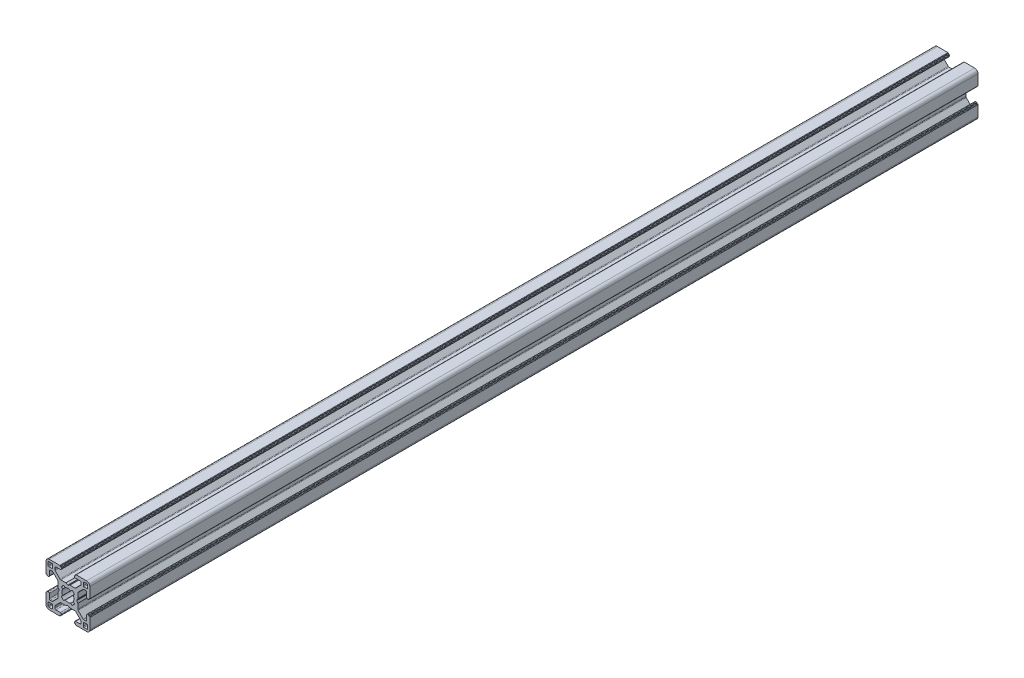
SolidWorks part; units mm, degrees
material "6063-O, Barra estrusa (SS)"
ref_plane "Piano frontale" through (0, 0, 0) normal (0, 0, 1) x (1, 0, 0)
ref_plane "Piano superiore" through (0, 0, 0) normal (0, 1, 0) x (1, 0, 0)
ref_plane "Piano destro" through (0, 0, 0) normal (1, 0, 0) x (0, 0, -1)
ref_plane "Piano1" through (0, 0, 100) normal (0, 0, 1) x (1, 0, 0)
sketch "Schizzo1" plane through (0, 0, 100) normal (0, 0, 1) x (1, 0, 0)
  line L0 (-1.9139, 2.9896) -> (-1.2582, 2.4453)
  line L1 (1.2582, 2.4453) -> (1.9139, 2.9896)
  line L2 (2.9922, 1.9099) -> (2.4453, 1.2582)
  line L3 (2.4453, -1.2582) -> (2.9922, -1.9099)
  line L4 (1.9139, -2.9896) -> (1.2582, -2.4453)
  line L5 (-1.2582, -2.4453) -> (-1.9139, -2.9896)
  line L6 (-2.9922, -1.9099) -> (-2.4453, -1.2582)
  line L7 (-2.4453, 1.2582) -> (-2.9922, 1.9099)
  line L8 (-9.3, 3) -> (-9, 3)
  line L9 (-8.5, 3.5) -> (-8.5, 5.5)
  line L10 (-8, 6) -> (-7.2678, 6)
  line L11 (-6.9142, 5.8536) -> (-4.6464, 3.5858)
  line L12 (-4.5, 3.2322) -> (-4.5, 0.9536)
  line L13 (-4.4732, 0.8536) -> (-4.0381, 0.1)
  line L14 (-4.0381, -0.1) -> (-4.4732, -0.8536)
  line L15 (-4.5, -0.9536) -> (-4.5, -3.2322)
  line L16 (-4.6464, -3.5858) -> (-6.9142, -5.8536)
  line L17 (-7.2678, -6) -> (-8, -6)
  line L18 (-8.5, -5.5) -> (-8.5, -3.5)
  line L19 (-9, -3) -> (-9.3, -3)
  line L20 (-9.5, -3.2) -> (-9.5, -3.35)
  line L21 (-9.7, -3.55) -> (-9.8, -3.55)
  line L22 (-10, -3.75) -> (-10, -8.5)
  line L23 (-8.5, -10) -> (-3.75, -10)
  line L24 (-3.55, -9.8) -> (-3.55, -9.7)
  line L25 (-3.35, -9.5) -> (-3.2, -9.5)
  line L26 (-3, -9.3) -> (-3, -9)
  line L27 (-3.5, -8.5) -> (-5.5, -8.5)
  line L28 (-6, -8) -> (-6, -7.2678)
  line L29 (-5.8536, -6.9142) -> (-3.5858, -4.6464)
  line L30 (-3.2322, -4.5) -> (-0.9536, -4.5)
  line L31 (-0.8536, -4.4732) -> (-0.1, -4.0381)
  line L32 (0.1, -4.0381) -> (0.8536, -4.4732)
  line L33 (0.9536, -4.5) -> (3.2322, -4.5)
  line L34 (3.5858, -4.6464) -> (5.8536, -6.9142)
  line L35 (6, -7.2678) -> (6, -8)
  line L36 (5.5, -8.5) -> (3.5, -8.5)
  line L37 (3, -9) -> (3, -9.3)
  line L38 (3.2, -9.5) -> (3.35, -9.5)
  line L39 (3.55, -9.7) -> (3.55, -9.8)
  line L40 (3.75, -10) -> (8.5, -10)
  line L41 (10, -8.5) -> (10, -3.75)
  line L42 (9.8, -3.55) -> (9.7, -3.55)
  line L43 (9.5, -3.35) -> (9.5, -3.2)
  line L44 (9.3, -3) -> (9, -3)
  line L45 (8.5, -3.5) -> (8.5, -5.5)
  line L46 (8, -6) -> (7.2678, -6)
  line L47 (6.9142, -5.8536) -> (4.6464, -3.5858)
  line L48 (4.5, -3.2322) -> (4.5, -0.9536)
  line L49 (4.4732, -0.8536) -> (4.0381, -0.1)
  line L50 (4.0381, 0.1) -> (4.4732, 0.8536)
  line L51 (4.5, 0.9536) -> (4.5, 3.2322)
  line L52 (4.6464, 3.5858) -> (6.9142, 5.8536)
  line L53 (7.2678, 6) -> (8, 6)
  line L54 (8.5, 5.5) -> (8.5, 3.5)
  line L55 (9, 3) -> (9.3, 3)
  line L56 (9.5, 3.2) -> (9.5, 3.35)
  line L57 (9.7, 3.55) -> (9.8, 3.55)
  line L58 (10, 3.75) -> (10, 8.5)
  line L59 (8.5, 10) -> (3.75, 10)
  line L60 (3.55, 9.8) -> (3.55, 9.7)
  line L61 (3.35, 9.5) -> (3.2, 9.5)
  line L62 (3, 9.3) -> (3, 9)
  line L63 (3.5, 8.5) -> (5.5, 8.5)
  line L64 (6, 8) -> (6, 7.2678)
  line L65 (5.8536, 6.9142) -> (3.5858, 4.6464)
  line L66 (3.2322, 4.5) -> (0.9536, 4.5)
  line L67 (0.8536, 4.4732) -> (0.1, 4.0381)
  line L68 (-0.1, 4.0381) -> (-0.8536, 4.4732)
  line L69 (-0.9536, 4.5) -> (-3.2322, 4.5)
  line L70 (-3.5858, 4.6464) -> (-5.8536, 6.9142)
  line L71 (-6, 7.2678) -> (-6, 8)
  line L72 (-5.5, 8.5) -> (-3.5, 8.5)
  line L73 (-3, 9) -> (-3, 9.3)
  line L74 (-3.2, 9.5) -> (-3.35, 9.5)
  line L75 (-3.55, 9.7) -> (-3.55, 9.8)
  line L76 (-3.75, 10) -> (-8.5, 10)
  line L77 (-10, 8.5) -> (-10, 3.75)
  line L78 (-9.8, 3.55) -> (-9.7, 3.55)
  line L79 (-9.5, 3.35) -> (-9.5, 3.2)
  line L80 (8.7, 7) -> (7.3, 7)
  line L81 (-7.3, 7) -> (-8.7, 7)
  line L82 (-7, 7.3) -> (-7, 8.7)
  line L83 (-7.3, 9) -> (-8.7, 9)
  line L84 (-9, 7.3) -> (-9, 8.7)
  line L85 (9, 7.3) -> (9, 8.7)
  line L86 (8.7, 9) -> (7.3, 9)
  line L87 (7, 7.3) -> (7, 8.7)
  line L88 (8.7, -9) -> (7.3, -9)
  line L89 (9, -8.7) -> (9, -7.3)
  line L90 (8.7, -7) -> (7.3, -7)
  line L91 (7, -8.7) -> (7, -7.3)
  line L92 (-7.3, -9) -> (-8.7, -9)
  line L93 (-7, -8.7) -> (-7, -7.3)
  line L94 (-7.3, -7) -> (-8.7, -7)
  line L95 (-9, -8.7) -> (-9, -7.3)
  arc A0 (-1.2582, 2.4453) -> (1.2582, 2.4453) centre (0, 0) cw
  arc A1 (1.9139, 2.9896) -> (2.9922, 1.9099) centre (0, 0) cw
  arc A2 (2.4453, 1.2582) -> (2.4453, -1.2582) centre (0, 0) cw
  arc A3 (2.9922, -1.9099) -> (1.9139, -2.9896) centre (0, 0) cw
  arc A4 (1.2582, -2.4453) -> (-1.2582, -2.4453) centre (0, 0) cw
  arc A5 (-1.9139, -2.9896) -> (-2.9922, -1.9099) centre (0, 0) cw
  arc A6 (-2.4453, -1.2582) -> (-2.4453, 1.2582) centre (0, 0) cw
  arc A7 (-2.9922, 1.9099) -> (-1.9139, 2.9896) centre (0, 0) cw
  arc A8 (-9.5, 3.2) -> (-9.3, 3) centre (-9.3, 3.2) ccw
  arc A9 (-9, 3) -> (-8.5, 3.5) centre (-9, 3.5) ccw
  arc A10 (-8.5, 5.5) -> (-8, 6) centre (-8, 5.5) cw
  arc A11 (-7.2678, 6) -> (-6.9142, 5.8536) centre (-7.2678, 5.5) cw
  arc A12 (-4.6464, 3.5858) -> (-4.5, 3.2322) centre (-5, 3.2322) cw
  arc A13 (-4.5, 0.9536) -> (-4.4732, 0.8536) centre (-4.3, 0.9536) ccw
  arc A14 (-4.0381, 0.1) -> (-4.0381, -0.1) centre (-4.2113, 0) cw
  arc A15 (-4.4732, -0.8536) -> (-4.5, -0.9536) centre (-4.3, -0.9536) ccw
  arc A16 (-4.5, -3.2322) -> (-4.6464, -3.5858) centre (-5, -3.2322) cw
  arc A17 (-6.9142, -5.8536) -> (-7.2678, -6) centre (-7.2678, -5.5) cw
  arc A18 (-8, -6) -> (-8.5, -5.5) centre (-8, -5.5) cw
  arc A19 (-8.5, -3.5) -> (-9, -3) centre (-9, -3.5) ccw
  arc A20 (-9.3, -3) -> (-9.5, -3.2) centre (-9.3, -3.2) ccw
  arc A21 (-9.5, -3.35) -> (-9.7, -3.55) centre (-9.7, -3.35) cw
  arc A22 (-9.8, -3.55) -> (-10, -3.75) centre (-9.8, -3.75) ccw
  arc A23 (-10, -8.5) -> (-8.5, -10) centre (-8.5, -8.5) ccw
  arc A24 (-3.75, -10) -> (-3.55, -9.8) centre (-3.75, -9.8) ccw
  arc A25 (-3.55, -9.7) -> (-3.35, -9.5) centre (-3.35, -9.7) cw
  arc A26 (-3.2, -9.5) -> (-3, -9.3) centre (-3.2, -9.3) ccw
  arc A27 (-3, -9) -> (-3.5, -8.5) centre (-3.5, -9) ccw
  arc A28 (-5.5, -8.5) -> (-6, -8) centre (-5.5, -8) cw
  arc A29 (-6, -7.2678) -> (-5.8536, -6.9142) centre (-5.5, -7.2678) cw
  arc A30 (-3.5858, -4.6464) -> (-3.2322, -4.5) centre (-3.2322, -5) cw
  arc A31 (-0.9536, -4.5) -> (-0.8536, -4.4732) centre (-0.9536, -4.3) ccw
  arc A32 (-0.1, -4.0381) -> (0.1, -4.0381) centre (0, -4.2113) cw
  arc A33 (0.8536, -4.4732) -> (0.9536, -4.5) centre (0.9536, -4.3) ccw
  arc A34 (3.2322, -4.5) -> (3.5858, -4.6464) centre (3.2322, -5) cw
  arc A35 (5.8536, -6.9142) -> (6, -7.2678) centre (5.5, -7.2678) cw
  arc A36 (6, -8) -> (5.5, -8.5) centre (5.5, -8) cw
  arc A37 (3.5, -8.5) -> (3, -9) centre (3.5, -9) ccw
  arc A38 (3, -9.3) -> (3.2, -9.5) centre (3.2, -9.3) ccw
  arc A39 (3.35, -9.5) -> (3.55, -9.7) centre (3.35, -9.7) cw
  arc A40 (3.55, -9.8) -> (3.75, -10) centre (3.75, -9.8) ccw
  arc A41 (8.5, -10) -> (10, -8.5) centre (8.5, -8.5) ccw
  arc A42 (10, -3.75) -> (9.8, -3.55) centre (9.8, -3.75) ccw
  arc A43 (9.7, -3.55) -> (9.5, -3.35) centre (9.7, -3.35) cw
  arc A44 (9.5, -3.2) -> (9.3, -3) centre (9.3, -3.2) ccw
  arc A45 (9, -3) -> (8.5, -3.5) centre (9, -3.5) ccw
  arc A46 (8.5, -5.5) -> (8, -6) centre (8, -5.5) cw
  arc A47 (7.2678, -6) -> (6.9142, -5.8536) centre (7.2678, -5.5) cw
  arc A48 (4.6464, -3.5858) -> (4.5, -3.2322) centre (5, -3.2322) cw
  arc A49 (4.5, -0.9536) -> (4.4732, -0.8536) centre (4.3, -0.9536) ccw
  arc A50 (4.0381, -0.1) -> (4.0381, 0.1) centre (4.2113, 0) cw
  arc A51 (4.4732, 0.8536) -> (4.5, 0.9536) centre (4.3, 0.9536) ccw
  arc A52 (4.5, 3.2322) -> (4.6464, 3.5858) centre (5, 3.2322) cw
  arc A53 (6.9142, 5.8536) -> (7.2678, 6) centre (7.2678, 5.5) cw
  arc A54 (8, 6) -> (8.5, 5.5) centre (8, 5.5) cw
  arc A55 (8.5, 3.5) -> (9, 3) centre (9, 3.5) ccw
  arc A56 (9.3, 3) -> (9.5, 3.2) centre (9.3, 3.2) ccw
  arc A57 (9.5, 3.35) -> (9.7, 3.55) centre (9.7, 3.35) cw
  arc A58 (9.8, 3.55) -> (10, 3.75) centre (9.8, 3.75) ccw
  arc A59 (10, 8.5) -> (8.5, 10) centre (8.5, 8.5) ccw
  arc A60 (3.75, 10) -> (3.55, 9.8) centre (3.75, 9.8) ccw
  arc A61 (3.55, 9.7) -> (3.35, 9.5) centre (3.35, 9.7) cw
  arc A62 (3.2, 9.5) -> (3, 9.3) centre (3.2, 9.3) ccw
  arc A63 (3, 9) -> (3.5, 8.5) centre (3.5, 9) ccw
  arc A64 (5.5, 8.5) -> (6, 8) centre (5.5, 8) cw
  arc A65 (6, 7.2678) -> (5.8536, 6.9142) centre (5.5, 7.2678) cw
  arc A66 (3.5858, 4.6464) -> (3.2322, 4.5) centre (3.2322, 5) cw
  arc A67 (0.9536, 4.5) -> (0.8536, 4.4732) centre (0.9536, 4.3) ccw
  arc A68 (0.1, 4.0381) -> (-0.1, 4.0381) centre (0, 4.2113) cw
  arc A69 (-0.8536, 4.4732) -> (-0.9536, 4.5) centre (-0.9536, 4.3) ccw
  arc A70 (-3.2322, 4.5) -> (-3.5858, 4.6464) centre (-3.2322, 5) cw
  arc A71 (-5.8536, 6.9142) -> (-6, 7.2678) centre (-5.5, 7.2678) cw
  arc A72 (-6, 8) -> (-5.5, 8.5) centre (-5.5, 8) cw
  arc A73 (-3.5, 8.5) -> (-3, 9) centre (-3.5, 9) ccw
  arc A74 (-3, 9.3) -> (-3.2, 9.5) centre (-3.2, 9.3) ccw
  arc A75 (-3.35, 9.5) -> (-3.55, 9.7) centre (-3.35, 9.7) cw
  arc A76 (-3.55, 9.8) -> (-3.75, 10) centre (-3.75, 9.8) ccw
  arc A77 (-8.5, 10) -> (-10, 8.5) centre (-8.5, 8.5) ccw
  arc A78 (-10, 3.75) -> (-9.8, 3.55) centre (-9.8, 3.75) ccw
  arc A79 (-9.7, 3.55) -> (-9.5, 3.35) centre (-9.7, 3.35) cw
  arc A80 (-8.7, 7) -> (-9, 7.3) centre (-8.7, 7.3) cw
  arc A81 (-7, 8.7) -> (-7.3, 9) centre (-7.3, 8.7) ccw
  arc A82 (-7.3, 7) -> (-7, 7.3) centre (-7.3, 7.3) ccw
  arc A83 (-8.7, 9) -> (-9, 8.7) centre (-8.7, 8.7) ccw
  arc A84 (7.3, 7) -> (7, 7.3) centre (7.3, 7.3) cw
  arc A85 (9, 8.7) -> (8.7, 9) centre (8.7, 8.7) ccw
  arc A86 (8.7, 7) -> (9, 7.3) centre (8.7, 7.3) ccw
  arc A87 (7.3, 9) -> (7, 8.7) centre (7.3, 8.7) ccw
  arc A88 (7.3, -9) -> (7, -8.7) centre (7.3, -8.7) cw
  arc A89 (9, -7.3) -> (8.7, -7) centre (8.7, -7.3) ccw
  arc A90 (8.7, -9) -> (9, -8.7) centre (8.7, -8.7) ccw
  arc A91 (7.3, -7) -> (7, -7.3) centre (7.3, -7.3) ccw
  arc A92 (-8.7, -9) -> (-9, -8.7) centre (-8.7, -8.7) cw
  arc A93 (-7, -7.3) -> (-7.3, -7) centre (-7.3, -7.3) ccw
  arc A94 (-7.3, -9) -> (-7, -8.7) centre (-7.3, -8.7) ccw
  arc A95 (-8.7, -7) -> (-9, -7.3) centre (-8.7, -7.3) ccw
  dimension "D1" = 0.3
  dimension "D2" = 1
  dimension "D3" = 1
  dimension "D4" = 1
  dimension "D7" = 1
  dimension "D8" = 1
  dimension "D9" = 1
  dimension "D10" = 1
  dimension "D5" = 2
  dimension "D6" = 2
extrude "Estrusione-Estrusione1" add sketch "Schizzo1" against normal blind 405
